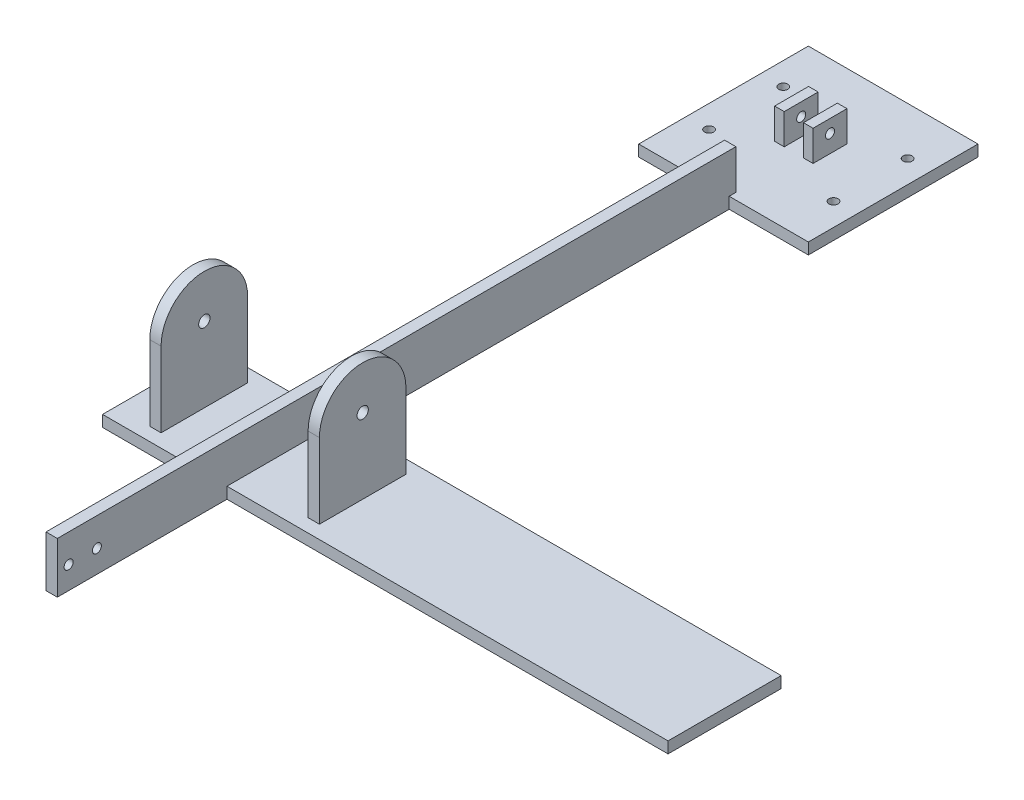
SolidWorks part; units mm, degrees
ref_plane "Front Plane" through (0, 0, 0) normal (0, 0, 1) x (1, 0, 0)
ref_plane "Top Plane" through (0, 0, 0) normal (0, 1, 0) x (1, 0, 0)
ref_plane "Right Plane" through (0, 0, 0) normal (1, 0, 0) x (0, 0, -1)
sketch "Sketch2" plane through (0, 0, 0) normal (0, 1, 0) x (1, 0, 0)
  line L0 (-75, 150) -> (-75, 0) construction
  line L5 (0, 0) -> (-150, 0)
  line L6 (0, 0) -> (0, 150)
  line L7 (0, 150) -> (-150, 150)
  line L8 (-150, 0) -> (-150, 150)
  line L9 (-150, 75) -> (0, 75) construction
  circle A0 centre (-130, 42.2411) radius 4
  circle A1 centre (-20, 42.2411) radius 4
  circle A2 centre (-20, 107.7589) radius 4
  circle A3 centre (-130, 107.7589) radius 4
  dimension "D3" = 8
  dimension "D4" = 8
  dimension "D1" = 150
  dimension "D2" = 150
  dimension "D5" = 20
  dimension "D6" = 20
extrude "Boss-Extrude2" add sketch "Sketch2" along normal blind 10
sketch "Sketch3" plane through (0, 0, 0) normal (0, 1, 0) x (1, 0, 0)
  line L0 (-150, 150) -> (-150, 0) construction
  line L1 (-80, 5.9547) -> (-70, 5.9547)
  line L2 (-80, 5.9547) -> (-80, -594.0453)
  line L3 (-80, -594.0453) -> (-70, -594.0453)
  line L4 (-70, 5.9547) -> (-70, -594.0453)
  dimension "D1" = 10
  dimension "D2" = 70
  dimension "D3" = 600
extrude "Boss-Extrude3" add sketch "Sketch3" along normal blind 45
sketch "Sketch4" plane through (0, 0, 0) normal (0, 1, 0) x (1, 0, 0)
  line L1 (-180, -344.0453) -> (320, -344.0453)
  line L2 (-180, -344.0453) -> (-180, -444.0453)
  line L3 (-180, -444.0453) -> (320, -444.0453)
  line L4 (320, -344.0453) -> (320, -444.0453)
  line L5 (-80, -594.0453) -> (-70, -594.0453) construction
  line L6 (-80, 5.9547) -> (-80, -594.0453) construction
  dimension "D1" = 100
  dimension "D2" = 150
  dimension "D3" = 500
  dimension "D4" = 100
extrude "Boss-Extrude4" add sketch "Sketch4" along normal blind 10
sketch "Sketch5" plane through (0, 0, 0) normal (1, 0, 0) x (0, 0, -1)
  line L0 (-432.2853, 10) -> (-432.2853, 76.3488)
  line L1 (-444.0453, 10) -> (-344.0453, 10) construction
  line L2 (-394.0453, 10) -> (-394.0453, 219.1776) construction
  line L3 (-444.0453, 10) -> (-344.0453, 10) construction
  line L4 (-355.8053, 10) -> (-355.8053, 76.3488)
  line L5 (-432.2853, 10) -> (-355.8053, 10)
  arc A0 (-432.2853, 76.3488) -> (-394.0453, 114.5888) centre (-394.0453, 76.3488) cw
  arc A1 (-355.8053, 76.3488) -> (-394.0453, 114.5888) centre (-394.0453, 76.3488) ccw
  circle A2 centre (-394.0453, 76.3488) radius 5
  dimension "D2" = 10
  dimension "D1" = 38.24
extrude "Boss-Extrude5" add sketch "Sketch5" against normal blind 10
ref_plane "Plane1" through (-75, 0, 0) normal (1, 0, 0) x (0, 0, -1)
mirror "Mirror1" about plane through (-75, 0, 0) normal (1, 0, 0) of "Boss-Extrude5"
ref_plane "Plane2" through (-58, 0, 0) normal (1, 0, 0) x (0, 0, -1)
sketch "Sketch7" plane through (-58, 0, 0) normal (1, 0, 0) x (0, 0, -1)
  line L0 (0, 10) -> (150, 10) construction
  line L1 (77.165, 10) -> (77.165, 69.6913) construction
  line L2 (62.165, 10) -> (92.165, 10)
  line L3 (62.165, 10) -> (62.165, 37)
  line L4 (62.165, 37) -> (92.165, 37)
  line L5 (92.165, 10) -> (92.165, 37)
  circle A0 centre (77.165, 25.5245) radius 4
  dimension "D2" = 8
  dimension "D1" = 27
  dimension "15" = 15
extrude "Boss-Extrude6" add sketch "Sketch7" against normal blind 8.5
mirror "Mirror2" about plane through (-75, 0, 0) normal (1, 0, 0) of "Boss-Extrude6"
sketch "Sketch8" plane through (-70, 0, 0) normal (1, 0, 0) x (0, 0, -1)
  line L0 (-594.0453, 45) -> (-594.0453, 0) construction
  circle A0 centre (-584.0453, 20) radius 4
  circle A1 centre (-559.0453, 20) radius 4
  dimension "D1" = 8
  dimension "D2" = 8
  dimension "D3" = 10
  dimension "D4" = 25
extrude "Cut-Extrude1" cut sketch "Sketch8" against normal through all
